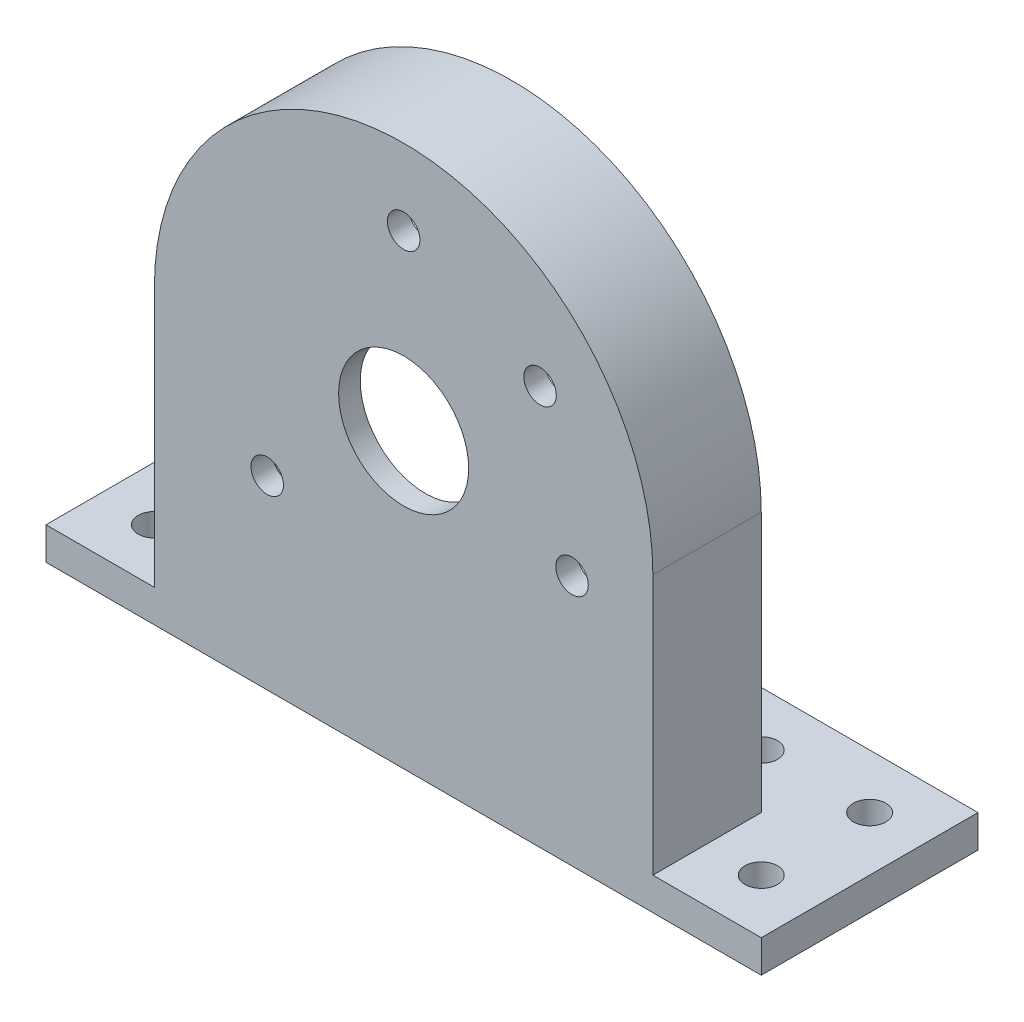
SolidWorks part; units mm, degrees
ref_plane "前视基准面" through (0, 0, 0) normal (0, 0, 1) x (1, 0, 0)
ref_plane "上视基准面" through (0, 0, 0) normal (0, 1, 0) x (1, 0, 0)
ref_plane "右视基准面" through (0, 0, 0) normal (1, 0, 0) x (0, 0, -1)
other "Configuration Table"
sketch "草图1" plane through (0, 0, 0) normal (0, 0, 1) x (1, 0, 0)
  line L0 (-23, 0) -> (-23, -27)
  line L1 (-23, -27) -> (23, -27)
  line L2 (23, -27) -> (23, 0)
  arc A1 (23, 0) -> (-23, 0) centre (0, 0) ccw
  dimension "D1" = 27
  dimension "D2" = 23
extrude "凸台-拉伸1" add sketch "草图1" along normal blind 20
sketch "草图2" plane through (0, 0, 0) normal (0, 0, -1) x (-1, 0, 0)
  line L0 (-23, -24) -> (23, -24)
  line L1 (23, 0) -> (23, -27) construction
  line L2 (-23, -27) -> (-23, 0) construction
  line L3 (-23, 0) -> (-23, -27)
  line L4 (-23, -27) -> (23, -27)
  line L5 (23, -27) -> (23, 0)
  line L6 (-23, 0) -> (-23, -24)
  line L8 (23, -24) -> (23, 0)
  arc A1 (23, 0) -> (-23, 0) centre (0, 0) ccw
  arc A2 (23, 0) -> (-23, 0) centre (0, 0) ccw
  dimension "D2" = 24
  dimension "D1" = 0
extrude "切除-拉伸1" cut sketch "草图2" against normal blind 10
sketch "草图3" plane through (0, 0, 10) normal (0, 0, -1) x (-1, 0, 0)
  circle A0 centre (0, 0) radius 21
extrude "切除-拉伸2" cut sketch "草图3" against normal blind 8
sketch "草图6" plane through (0, -27, 0) normal (0, -1, 0) x (1, 0, 0)
  line L0 (-23, 20) -> (-23, 0) construction
  line L1 (-23, 20) -> (23, 20) construction
  line L2 (0, -55) -> (0, 55) construction
  line L3 (-27.5378, 10) -> (27.2593, 10) construction
  circle A0 centre (-18, 15) radius 1.5
  circle A1 centre (18, 15) radius 1.5
  circle A2 centre (18, 5) radius 1.5
  circle A3 centre (-18, 5) radius 1.5
  dimension "D1" = 5
  dimension "D2" = 5
  dimension "D3" = 10
extrude "切除-拉伸3" cut sketch "草图6" against normal blind 5
sketch "草图7" plane through (0, 0, 20) normal (0, 0, 1) x (1, 0, 0)
  circle A0 centre (0, 16) radius 1.5 construction
  circle A1 centre (0, 16) radius 1.5
  circle A2 centre (12.5891, 9.875) radius 1.5 construction
  circle A3 centre (12.5891, 9.875) radius 1.5
  circle A4 centre (-12.5891, -9.875) radius 1.5 construction
  circle A5 centre (15.5396, -3.8105) radius 1.5 construction
  circle A6 centre (-12.5891, -9.875) radius 1.5
  circle A7 centre (15.5396, -3.8105) radius 1.5
extrude "切除-拉伸6" cut sketch "草图7" against normal blind 3
sketch "草图8" plane through (0, 0, 18) normal (0, 0, -1) x (-1, 0, 0)
  circle A1 centre (0, 0) radius 6
  circle A2 centre (0, 0) radius 6
  dimension "D1" = 0
extrude "切除-拉伸7" cut sketch "草图8" against normal blind 3
sketch "草图9" plane through (0, -27, 0) normal (0, -1, 0) x (1, 0, 0)
  line L0 (0, -11) -> (0, 11) construction
  line L1 (23, 20) -> (33, 20)
  line L2 (23, 20) -> (23, 0)
  line L3 (23, 0) -> (33, 0)
  line L4 (33, 20) -> (33, 0)
  line L5 (-33, 20) -> (-33, 0)
  line L6 (-23, 0) -> (-33, 0)
  line L7 (-23, 20) -> (-23, 0)
  line L8 (-23, 20) -> (-33, 20)
  line L9 (18, 15) -> (34.065, 15) construction
  line L10 (28, 20) -> (28, -1.2077) construction
  line L11 (19.5, 5) -> (34.065, 5) construction
  circle A2 centre (28, 15) radius 1.5
  circle A5 centre (28, 5) radius 1.5
  circle A6 centre (-28, 15) radius 1.5
  circle A7 centre (-28, 5) radius 1.5
  circle A8 centre (18, 5) radius 1.5 construction
  point P29 (28, 15)
  point P30 (28, 5)
  dimension "D1" = 10
  dimension "D2" = 20
extrude "凸台-拉伸2" add sketch "草图9" against normal blind 3
